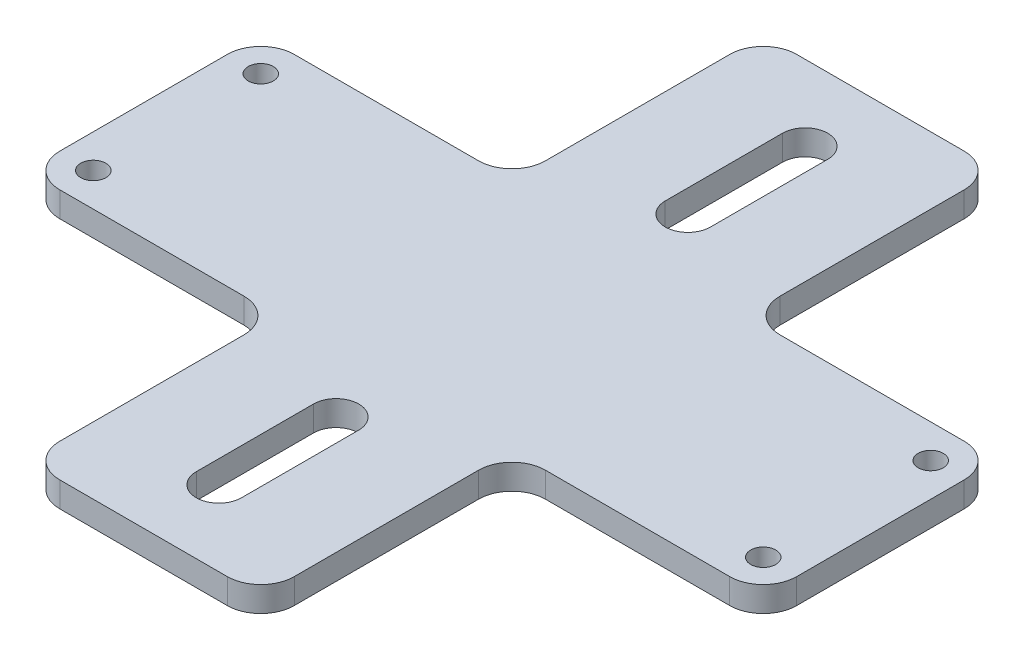
SolidWorks part; units mm, degrees
ref_plane "前视基准面" through (0, 0, 0) normal (0, 0, 1) x (1, 0, 0)
ref_plane "上视基准面" through (0, 0, 0) normal (0, 1, 0) x (1, 0, 0)
ref_plane "右视基准面" through (0, 0, 0) normal (1, 0, 0) x (0, 0, -1)
sketch "草图1" plane through (0, 0, 0) normal (0, 1, 0) x (1, 0, 0)
  line L1 (0, 30) -> (0, 35)
  line L2 (0, 35) -> (0, 30) construction
  line L3 (2.7, 35) -> (2.7, 30)
  line L4 (-44, 10) -> (-44, -10)
  line L10 (44, 10) -> (44, -10)
  line L11 (40, 14) -> (18, 14)
  line L12 (-2.7, 35) -> (-2.7, 30)
  line L13 (0, -35) -> (0, -30) construction
  line L14 (-2.7, -35) -> (-2.7, -30)
  line L15 (2.7, -35) -> (2.7, -30)
  line L16 (14, -40) -> (14, -18)
  line L17 (10, -44) -> (-10, -44)
  line L18 (-14, 40) -> (-14, 18)
  line L19 (10, 44) -> (-10, 44)
  line L20 (-40, -14) -> (-18, -14)
  line L21 (-44, -10) -> (-44, 10)
  line L22 (40, 14) -> (18, 14)
  line L23 (44, -10) -> (44, 10)
  line L24 (-14, 40) -> (-14, 18)
  line L25 (-10, 44) -> (10, 44)
  line L26 (14, -40) -> (14, -18)
  line L27 (-10, -44) -> (10, -44)
  line L29 (-14, -18) -> (-14, -40)
  line L30 (-18, 14) -> (-40, 14)
  line L31 (-18, 14) -> (-40, 14)
  line L32 (14, 18) -> (14, 40)
  line L33 (14, 18) -> (14, 40)
  line L34 (18, -14) -> (40, -14)
  line L35 (18, -14) -> (40, -14)
  circle A0 centre (40, 10) radius 1.5
  circle A1 centre (40, -10) radius 1.5
  circle A2 centre (-40, 10) radius 1.5
  circle A3 centre (-40, -10) radius 1.5
  arc A4 (-40, 14) -> (-44, 10) centre (-40, 10) ccw
  arc A5 (44, 10) -> (40, 14) centre (40, 10) ccw
  arc A6 (40, -14) -> (44, -10) centre (40, -10) ccw
  arc A7 (-44, -10) -> (-40, -14) centre (-40, -10) ccw
  arc A8 (2.7, 35) -> (-2.7, 35) centre (0, 35) ccw
  arc A9 (-2.7, 30) -> (2.7, 30) centre (0, 30) ccw
  arc A10 (-2.7, -35) -> (2.7, -35) centre (0, -35) ccw
  arc A11 (2.7, -30) -> (-2.7, -30) centre (0, -30) ccw
  arc A12 (10, -44) -> (14, -40) centre (10, -40) ccw
  arc A13 (-14, -40) -> (-10, -44) centre (-10, -40) ccw
  arc A14 (-10, 44) -> (-14, 40) centre (-10, 40) ccw
  arc A15 (14, 40) -> (10, 44) centre (10, 40) ccw
  arc A16 (-44, -10) -> (-40, -14) centre (-40, -10) ccw
  arc A17 (-40, 14) -> (-44, 10) centre (-40, 10) ccw
  arc A18 (44, 10) -> (40, 14) centre (40, 10) ccw
  arc A19 (40, -14) -> (44, -10) centre (40, -10) ccw
  arc A20 (-10, 44) -> (-14, 40) centre (-10, 40) ccw
  arc A21 (14, 40) -> (10, 44) centre (10, 40) ccw
  arc A22 (10, -44) -> (14, -40) centre (10, -40) ccw
  arc A23 (-14, -40) -> (-10, -44) centre (-10, -40) ccw
  arc A24 (-18, -14) -> (-14, -18) centre (-18, -18) cw
  arc A25 (-14, 18) -> (-18, 14) centre (-18, 18) cw
  arc A26 (18, 14) -> (14, 18) centre (18, 18) cw
  arc A27 (14, -18) -> (18, -14) centre (18, -18) cw
  point P3 (0, 32.5)
  point P9 (0, 0)
  point P30 (0, -32.5)
  point P36 (0, 0)
  point P73 (0, 0)
  point P87 (0, 0)
extrude "凸台-拉伸1" add sketch "草图1" along normal blind 5 contours L16 A27 L34 A6 L10 A5 L11 A26 L32 A15 L19 A14 L18 A25 L30 A4 L4 A7 L20 A24 L29 A13 L17 A12 A0 A1 A2 A3 A9 L12 A8 L3 A11 L15 A10 L14
sketch "草图2" plane through (0, 0, 0) normal (0, -1, 0) x (1, 0, 0)
  line L0 (0, -35) -> (0, -21) construction
  line L1 (-2.7, -35) -> (-2.7, -21)
  line L2 (2.7, -35) -> (2.7, -21)
  line L3 (0, 0) -> (-44, 0)
  line L4 (-44, -10) -> (-44, 10) construction
  line L5 (0, 35) -> (0, 21) construction
  line L6 (-2.7, 35) -> (-2.7, 21)
  line L7 (2.7, 35) -> (2.7, 21)
  arc A0 (-2.7, -35) -> (2.7, -35) centre (0, -35) ccw
  arc A1 (2.7, -21) -> (-2.7, -21) centre (0, -21) ccw
  arc A2 (-2.7, 35) -> (2.7, 35) centre (0, 35) cw
  arc A3 (2.7, 21) -> (-2.7, 21) centre (0, 21) cw
  point P4 (0, -28)
  point P15 (0, 28)
  arc M6 (-2.7, -30) -> (2.7, -30) centre (0, -30) cw
  line M7 (2.7, -30) -> (2.7, -35)
  arc M8 (2.7, -35) -> (-2.7, -35) centre (0, -35) cw
  line M9 (-2.7, -35) -> (-2.7, -30)
  arc M10 (2.7, 30) -> (-2.7, 30) centre (0, 30) cw
  line M11 (-2.7, 30) -> (-2.7, 35)
  arc M12 (-2.7, 35) -> (2.7, 35) centre (0, 35) cw
  line M13 (2.7, 35) -> (2.7, 30)
extrude "切除-拉伸1" cut sketch "草图2" against normal blind 10 contours L2 A1 L1 M6 | A3 L7 L6 M10 | M6 M9 M8 M7 | M10 M13 M12 M11
sketch "草图3" plane through (0, 0, 44) normal (0, 0, 1) x (1, 0, 0)
  line L0 (-44, 5) -> (-44, 3)
  line L1 (-44, 5) -> (53.6828, 5)
  line L2 (-44, 3) -> (53.6828, 3)
  line L3 (53.6828, 5) -> (53.6828, 3)
  line L4 (-44, 5) -> (-44, 0) construction
extrude "切除-拉伸2" cut sketch "草图3" against normal blind 94
